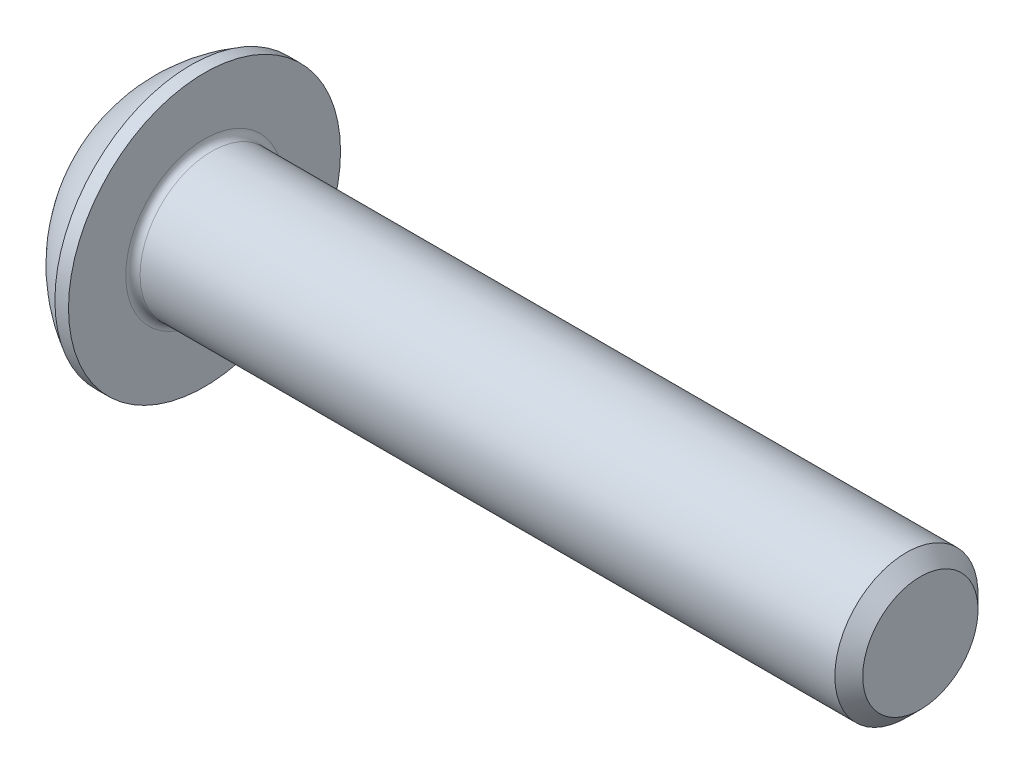
SolidWorks part; units mm, degrees
ref_plane "Plane1" through (0, 0, 0) normal (0, 0, 1) x (1, 0, 0)
ref_plane "Plane2" through (0, 0, 0) normal (0, 1, 0) x (1, 0, 0)
ref_plane "Plane3" through (0, 0, 0) normal (1, 0, 0) x (0, 0, -1)
other "Configuration Table"
sketch "BodySke" plane through (0, 0, 0) normal (0, 0, 1) x (1, 0, 0)
  line L0 (22.2, 0) -> (22.2, 1.61)
  line L1 (21.81, 2) -> (2.2, 2)
  line L2 (2.2, 2) -> (2.2, 3.8)
  line L3 (2.2, 3.8) -> (1.82, 3.8)
  line L4 (0, 0) -> (101.6, 0) construction
  line L5 (2.2, -3.8) -> (1.82, -3.8) construction
  line L6 (55.6768, -2) -> (2.2, -2) construction
  line L7 (22.2, 0) -> (0, 0)
  line L8 (0, 1.9) -> (0, -1.9) construction
  line L9 (0, 0) -> (0, 1.9)
  line L10 (22.2, 1.61) -> (21.81, 2)
  line L11 (22.2, -1.61) -> (21.81, -2) construction
  line L12 (2.9, 9.525) -> (2.9, -2) construction
  line L13 (2.2, 9.525) -> (2.2, -2) construction
  arc A1 (0, 1.9) -> (1.82, 3.8) centre (3.8853, 0) cw
  dimension "Diameter" = 4
  dimension "Head_dia" = 7.6
  dimension "D1" = 3.8
  dimension "Head_ht" = 2.2
  dimension "Head_side_ht" = 0.38
  dimension "Minor_dia" = 3.22
  dimension "Body_ch_ang" = 45
  dimension "Advance" = 0.7
revolve "BaseBody" add sketch "BodySke" angle 360 about L4
cosmetic thread "ThreadCosmetic" [suppressed] parameters "Thread_length"=18.6, "Thread_minor"=3.22
fillet "Fillet1" radius 0.2 1 edges at (2.2, 0, 2)
sketch "Sketch2" plane through (0, 0, 0) normal (0, 0, 1) x (1, 0, 0)
  line L0 (0, 1.25) -> (1.3, 1.25)
  line L1 (1.3, 1.25) -> (2.0217, 0)
  line L3 (2.0217, 0) -> (0, 0)
  line L4 (0, 0) -> (0, 1.25)
  line L5 (0, -1.25) -> (1.3, -1.25) construction
  line L6 (0, 0) -> (47.625, 0) construction
  dimension "D2" = 60
  dimension "PreBroach_depth" = 1.3
  dimension "PreBroach_dia" = 2.5
revolve "PreBroach" cut sketch "Sketch2" angle 360 about L6
sketch "Sketch3" plane through (0, 0, 0) normal (1, 0, 0) x (0, 0, -1)
  line L0 (-1.25, -0.7217) -> (-1.25, 0.7217)
  line L1 (-1.25, 0.7217) -> (0, 1.4434)
  line L2 (0, 1.4434) -> (1.25, 0.7217)
  line L3 (1.25, 0.7217) -> (1.25, -0.7217)
  line L4 (1.25, -0.7217) -> (0, -1.4434)
  line L5 (0, -1.4434) -> (-1.25, -0.7217)
  dimension "Hex_size" = 2.5
  dimension "D3" = 2.5
  dimension "D1" = 1.25
  dimension "D2" = 1.25
extrude "Hex" cut sketch "Sketch3" along normal blind 1.3
sketch "ThdSchSke" plane through (0, 0, 0) normal (0, 0, 1) x (1, 0, 0)
  line L0 (3.6, -1.61) -> (3.3269, -2)
  line L1 (3.6, -1.61) -> (3.8731, -2)
  line L2 (3.8731, -2) -> (3.8731, -2.5)
  line L3 (-3.175, 0) -> (5.1513, 0) construction
  line L5 (3.8731, -2.5) -> (3.3269, -2.5)
  line L6 (3.3269, -2.5) -> (3.3269, -2)
  dimension "Diameter" = 4
  dimension "Thread_minor" = 3.22
  dimension "SideAngle" = 55
  dimension "VeeAngle" = 70
  dimension "Overcut" = 5
  dimension "Start" = 3.6
revolve "ThreadSchematic" [suppressed] cut sketch "ThdSchSke" angle 360 about L3
pattern_linear "ThdSchPat" [suppressed]
equation "\"D1@BodySke\" = \"Head_dia@BodySke\" * .5"
equation "\"Thread_minor@ThreadCosmetic\" = \"Minor_dia@BodySke\""
equation "\"D1@Sketch3\" = \"Hex_size@Sketch3\" / 2"
equation "\"D2@Sketch3\" = \"D1@Sketch3\""
equation "\"D3@Sketch3\" = \"Hex_size@Sketch3\""
equation "\"Thread_length@ThreadCosmetic\" = ((sgn( (\"Length@BodySke\" - \"Advance@BodySke\" * 2.0) - \"Thread_nom@BodySke\" )-1)*( (\"Length@BodySke\" - \"Advance@BodySke\" * 2.0) - \"Thread_nom@BodySke\" ))/-2+ \"Thread_nom@BodySke\""
equation "\"Thread_minor@ThdSchSke\" = \"Minor_dia@BodySke\""
equation "\"Diameter@ThdSchSke\" = \"Diameter@BodySke\""
equation "\"Overcut@ThdSchSke\" = \"Diameter@BodySke\" * 1.25"
equation "\"Start@ThdSchSke\" = \"Head_ht@BodySke\" + \"Length@BodySke\" - \"Thread_length@ThreadCosmetic\"  '---Non-countersunk---"
equation "\"Num_threads@ThdSchPat\" = int( \"Thread_length@ThreadCosmetic\" / \"Advance@BodySke\" + 0.999 )  + 1"
equation "\"Advance@ThdSchPat\" = \"Thread_length@ThreadCosmetic\" /  (\"Num_threads@ThdSchPat\" - 1) 'relax it"
equation "\"Num_threads@ThdSchPat\" = \"Num_threads@ThdSchPat\" - sgn( \"Num_threads@ThdSchPat\" - 1) '---chamfered tips only---"
